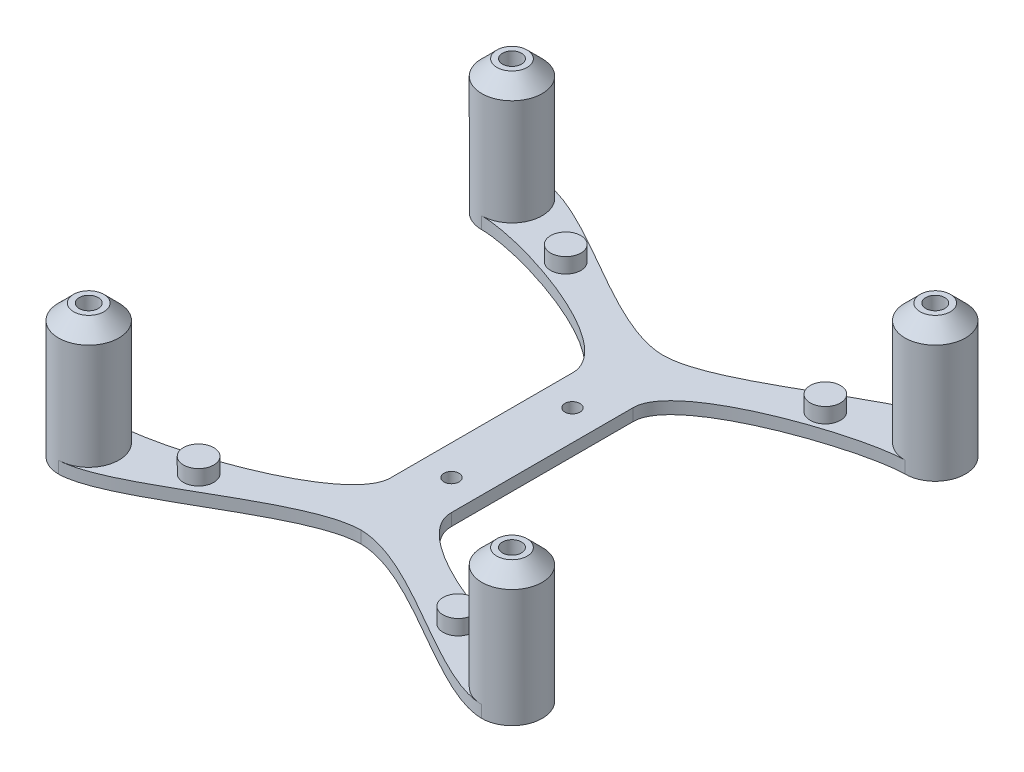
SolidWorks part; units mm, degrees
ref_plane "Front Plane" through (0, 0, 0) normal (0, 0, 1) x (1, 0, 0)
ref_plane "Top Plane" through (0, 0, 0) normal (0, 1, 0) x (1, 0, 0)
ref_plane "Right Plane" through (0, 0, 0) normal (1, 0, 0) x (0, 0, -1)
sketch "Sketch1" plane through (0, 0, 0) normal (0, 1, 0) x (1, 0, 0)
  line L0 (0, 0) -> (-6.35, 0)
  line L1 (-6.35, 0) -> (-6.35, 19.05)
  line L3 (0, 0) -> (0, 31.75)
  circle A0 centre (-44.45, 44.45) radius 6.35
  spline S0 degree 3 poles (0, 31.75) (-11.9435, 31.8274) (-34.0564, 50.716) (-44.45, 50.8) knots 0 0 0 0 1 1 1 1
  spline S1 degree 3 poles (-6.35, 19.05) (-6.1753, 28.394) (-35.1027, 38.0372) (-44.45, 38.1) knots 0 0 0 0 1 1 1 1
  dimension "D1" = 12.7
  dimension "D2" = 6.35
  dimension "D3" = 44.45
  dimension "D4" = 44.45
  dimension "D5" = 19.05
  dimension "D6" = 12.7
extrude "Boss-Extrude1" add sketch "Sketch1" along normal blind 2.54 contours S1 L1 L0 L3 S0 A0 | A0 S0
sketch "Sketch2" plane through (0, 2.54, 0) normal (0, 1, 0) x (1, 0, 0)
  circle A0 centre (-44.45, 44.45) radius 6.35
  arc A1 (-44.45, 50.8) -> (-44.45, 38.1) centre (-44.45, 44.45) ccw construction
extrude "Boss-Extrude2" add sketch "Sketch2" along normal blind 25.4
mirror "Mirror1" about plane through (0, 0, 0) normal (1, 0, 0) of "Boss-Extrude1", "Boss-Extrude2"
chamfer "Chamfer1" distance 3.175 angle 45 4 edges at (-44.45, 27.94, -38.1) (-44.45, 27.94, 38.1) (44.45, 27.94, -38.1) (44.45, 27.94, 38.1)
sketch "Sketch3" plane through (0, 2.54, 0) normal (0, 1, 0) x (1, 0, 0)
  line L0 (0, -12.7) -> (0, 12.7) construction
  circle A0 centre (0, 12.7) radius 1.5875
  circle A1 centre (0, -12.7) radius 1.5875
  dimension "D2" = 3.175
  dimension "D3" = 3.175
  dimension "D1" = 25.4
extrude "Cut-Extrude1" cut sketch "Sketch3" against normal through all
sketch "Sketch4" plane through (0, 27.94, 0) normal (0, 1, 0) x (1, 0, 0)
  circle A0 centre (-44.45, 44.45) radius 2
  dimension "D1" = 4
extrude "Cut-Extrude2" cut sketch "Sketch4" against normal blind 4.8
sketch "Sketch5" plane through (0, 23.14, 0) normal (0, 1, 0) x (1, 0, 0)
  circle A0 centre (-44.45, 44.45) radius 1.6
  dimension "D1" = 3.2
extrude "Cut-Extrude3" cut sketch "Sketch5" against normal through all
mirror "Mirror2" about plane through (0, 0, 0) normal (1, 0, 0) of "Cut-Extrude2", "Cut-Extrude3" second plane through (0, 0, 0) second plane normal (0, 0, 1)
sketch "Sketch6" plane through (0, 2.54, 0) normal (0, 1, 0) x (1, 0, 0)
  circle A0 centre (-27.2617, 38.5566) radius 3.175
  point P2 (-27.2617, 38.5566)
  dimension "D1" = 6.35
extrude "Boss-Extrude3" add sketch "Sketch6" along normal blind 3.175
mirror "Mirror3" about plane through (0, 0, 0) normal (1, 0, 0) of "Boss-Extrude3" second plane through (0, 0, 0) second plane normal (0, 0, 1)
